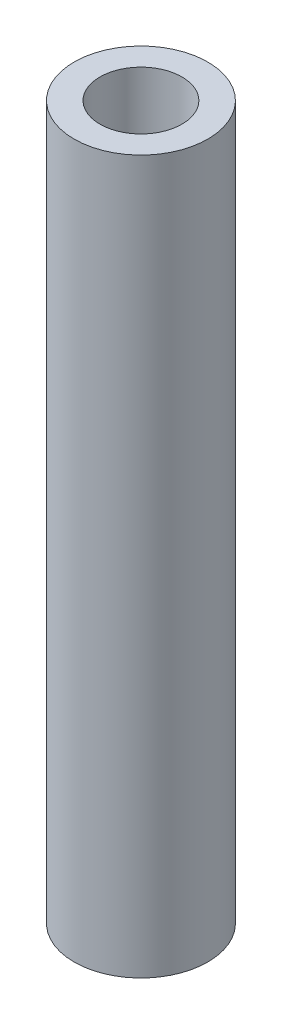
SolidWorks part; units mm, degrees
ref_plane "Front" through (0, 0, 0) normal (0, 0, 1) x (1, 0, 0)
ref_plane "Top" through (0, 0, 0) normal (0, 1, 0) x (1, 0, 0)
ref_plane "Right" through (0, 0, 0) normal (1, 0, 0) x (0, 0, -1)
sketch "Sketch1" plane through (0, 0, 0) normal (0, 1, 0) x (1, 0, 0)
  circle A0 centre (0, 0) radius 2.3812
  circle A1 centre (0, 0) radius 1.4605
  dimension "D1" = 4.7625
  dimension "D2" = 2.921
extrude "Boss-Extrude1" add sketch "Sketch1" along normal blind 25.4
